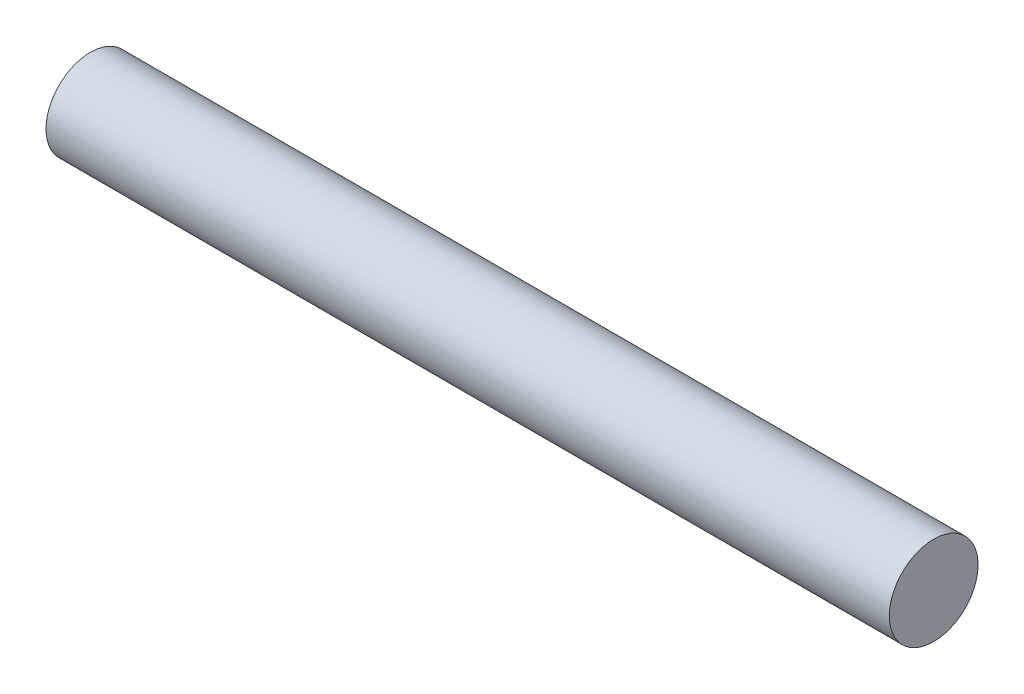
SolidWorks part; units mm, degrees
ref_plane "前视基准面" through (0, 0, 0) normal (0, 0, 1) x (1, 0, 0)
ref_plane "上视基准面" through (0, 0, 0) normal (0, 1, 0) x (1, 0, 0)
ref_plane "右视基准面" through (0, 0, 0) normal (1, 0, 0) x (0, 0, -1)
other "Configuration Table"
sketch "草图1" plane through (0, 0, 0) normal (0, 0, 1) x (1, 0, 0)
  line L0 (0, 0) -> (40.0305, 0) construction
  line L1 (0, 0) -> (0, 6)
  line L2 (0, 6) -> (114, 6)
  line L3 (114, 6) -> (114, 0)
  line L4 (0, 0) -> (114, 0)
  dimension "D1" = 6
  dimension "D2" = 114
revolve "旋转1" add sketch "草图1" angle 360 about L0
